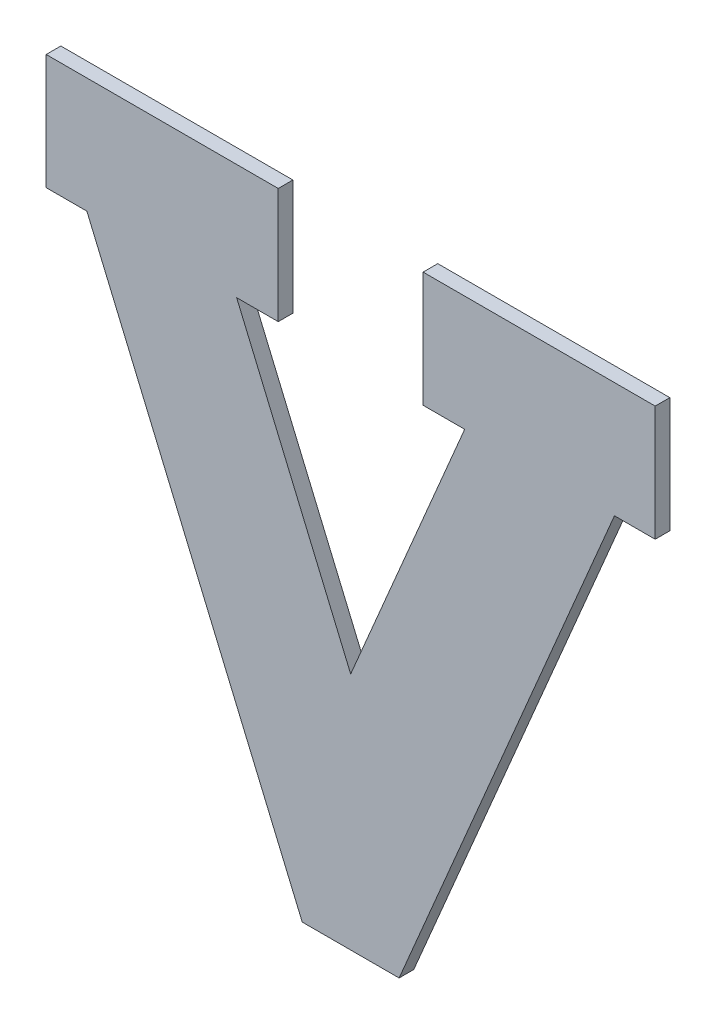
SolidWorks part; units mm, degrees
material "Cedar"
ref_plane "Front Plane" through (0, 0, 0) normal (0, 0, 1) x (1, 0, 0)
ref_plane "Top Plane" through (0, 0, 0) normal (0, 1, 0) x (1, 0, 0)
ref_plane "Right Plane" through (0, 0, 0) normal (1, 0, 0) x (0, 0, -1)
sketch "Sketch1" plane through (0, 0, 0) normal (0, 0, 1) x (1, 0, 0)
  point P0 (0, 0)
  line B0 (326.5754, 440.106) -> (356.1251, 440.106)
  line B1 (356.1251, 440.106) -> (276.5171, 252.3248)
  line B2 (276.5171, 252.3248) -> (196.9092, 440.106)
  line B3 (196.9092, 440.106) -> (226.4589, 440.106)
  line B4 (226.4589, 440.106) -> (226.4589, 565.4544)
  line B5 (226.4589, 565.4544) -> (0, 565.4544)
  line B6 (0, 565.4544) -> (0, 440.106)
  line B7 (0, 440.106) -> (39.5592, 440.106)
  line B8 (39.5592, 440.106) -> (226.1378, 0)
  line B9 (226.1378, 0) -> (326.8965, 0)
  line B10 (326.8965, 0) -> (513.4751, 440.106)
  line B11 (513.4751, 440.106) -> (553.0343, 440.106)
  line B12 (553.0343, 440.106) -> (553.0343, 565.4544)
  line B13 (553.0343, 565.4544) -> (326.5754, 565.4544)
  line B14 (326.5754, 565.4544) -> (326.5754, 440.106)
  line B15 (318.4864, 12.7) -> (234.5479, 12.7)
  line B16 (505.065, 452.806) -> (318.4864, 12.7)
  line B17 (540.3343, 452.806) -> (505.065, 452.806)
  line B18 (540.3343, 552.7544) -> (540.3343, 452.806)
  line B19 (339.2754, 552.7544) -> (540.3343, 552.7544)
  line B20 (339.2754, 452.806) -> (339.2754, 552.7544)
  line B21 (375.3033, 452.806) -> (339.2754, 452.806)
  line B22 (276.5171, 219.7869) -> (375.3033, 452.806)
  line B23 (177.731, 452.806) -> (276.5171, 219.7869)
  line B24 (213.7589, 452.806) -> (177.731, 452.806)
  line B25 (213.7589, 552.7544) -> (213.7589, 452.806)
  line B26 (12.7, 552.7544) -> (213.7589, 552.7544)
  line B27 (12.7, 452.806) -> (12.7, 552.7544)
  line B28 (47.9692, 452.806) -> (12.7, 452.806)
  line B29 (234.5479, 12.7) -> (47.9692, 452.806)
sketch_block_instance "V_Block-1"
sketch_block "V_Block"
extrude "Boss-Extrude1" add sketch "Sketch1" along normal blind 12.7 contours B29 B15 B16 B17 B18 B19 B20 B21 B22 B23 B24 B25 B26 B27 B28
